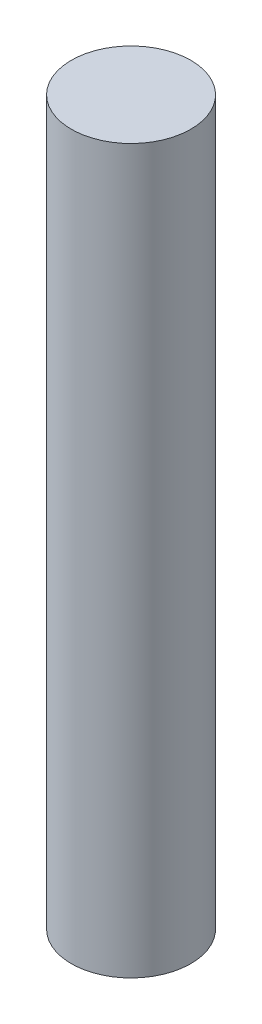
SolidWorks part; units mm, degrees
ref_plane "Front Plane" through (0, 0, 0) normal (0, 0, 1) x (1, 0, 0)
ref_plane "Top Plane" through (0, 0, 0) normal (0, 1, 0) x (1, 0, 0)
ref_plane "Right Plane" through (0, 0, 0) normal (1, 0, 0) x (0, 0, -1)
sketch "Sketch1" plane through (0, 0, 0) normal (0, 0, 1) x (1, 0, 0)
  line L0 (0, 0) -> (0, 18.14) construction
  line L1 (0, 18.14) -> (1.5, 18.14) construction
  line L2 (1.5, 18.14) -> (1.5, 0) construction
  line L3 (1.5, 0) -> (0, 0) construction
  line L4 (0, 0) -> (1.5, 0)
  line L5 (1.5, 0) -> (1.5, 18.14)
  line L6 (1.5, 18.14) -> (0, 18.14)
  line L7 (0, 0) -> (0, 18.14)
  dimension "D1" = 3
  dimension "D2" = 18.14
revolve "Revolve1" add sketch "Sketch1" angle 360 about L7
